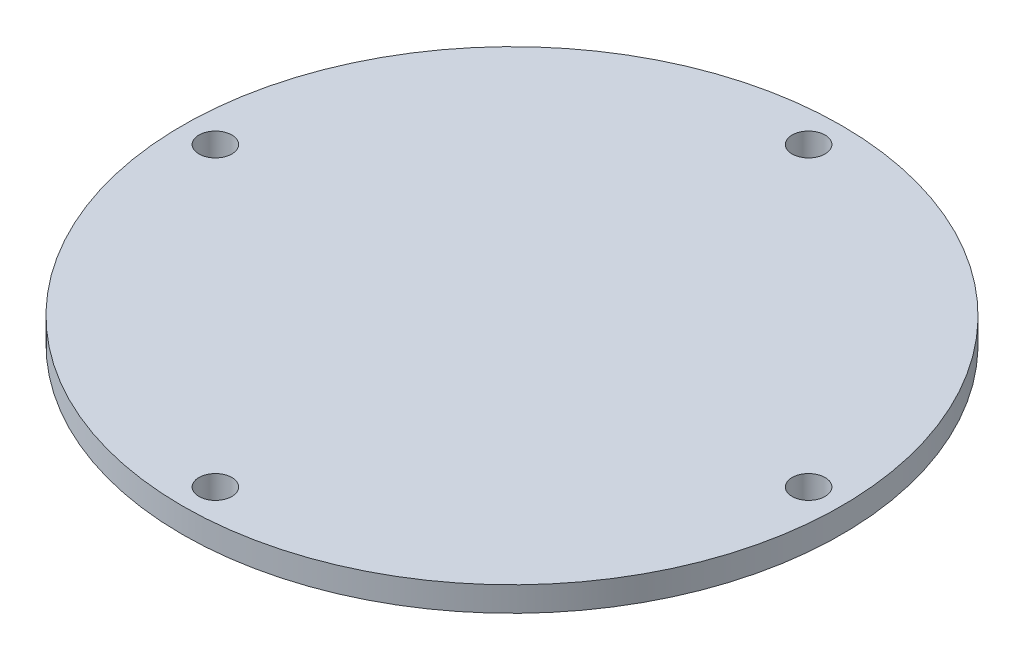
SolidWorks part; units mm, degrees
ref_plane "Front Plane" through (0, 0, 0) normal (0, 0, 1) x (1, 0, 0)
ref_plane "Top Plane" through (0, 0, 0) normal (0, 1, 0) x (1, 0, 0)
ref_plane "Right Plane" through (0, 0, 0) normal (1, 0, 0) x (0, 0, -1)
sketch "Sketch2" plane through (0, 0, 0) normal (0, 1, 0) x (1, 0, 0)
  line L0 (0, 40) -> (0, -40) construction
  line L2 (-31, 29) -> (31, 29)
  line L3 (-31, 29) -> (-31, -29)
  line L4 (-31, -29) -> (31, -29)
  line L5 (31, 29) -> (31, -29)
  line L6 (-31, 29) -> (31, -29) construction
  line L7 (-31, -29) -> (31, 29) construction
  circle A0 centre (0, 0) radius 40
  circle A2 centre (0, 36) radius 2
  circle A3 centre (36, 0) radius 2
  circle A4 centre (0, -36) radius 2
  circle A5 centre (-36, 0) radius 2
  point P16 (0, 0)
  dimension "D1" = 36
  dimension "D2" = 4
  dimension "D3" = 62
  dimension "D4" = 58
extrude "Boss-Extrude1" add sketch "Sketch2" along normal blind 3 contours L2 A0 A2 | L4 A0 L5 L2 L3 | L3 A0 A5 | L4 A0 A4 | L5 A0 A3
